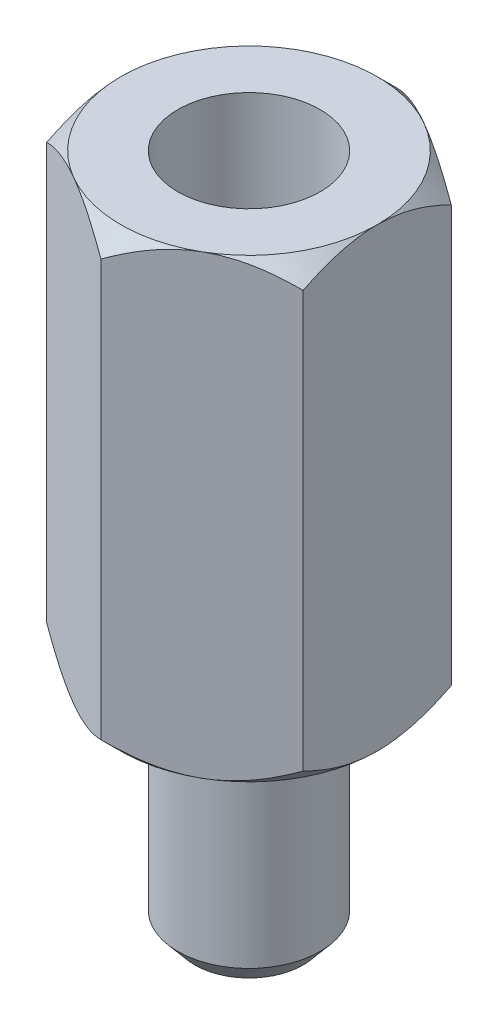
SolidWorks part; units mm, degrees
ref_plane "Front Plane" through (0, 0, 0) normal (0, 0, 1) x (1, 0, 0)
ref_plane "Top Plane" through (0, 0, 0) normal (0, 1, 0) x (1, 0, 0)
ref_plane "Right Plane" through (0, 0, 0) normal (1, 0, 0) x (0, 0, -1)
sketch "Sketch1" plane through (0, 0, 0) normal (0, 1, 0) x (1, 0, 0)
  circle A0 centre (0, 0) radius 1.25
  dimension "D1" = 2.5
extrude "Boss-Extrude1" add sketch "Sketch1" along normal blind 3.9
sketch "Sketch2" plane through (0, 3.9, 0) normal (0, 1, 0) x (1, 0, 0)
  line L1 (-2.25, 1.299) -> (-2.25, -1.299)
  line L2 (-2.25, -1.299) -> (0, -2.5981)
  line L3 (0, -2.5981) -> (2.25, -1.299)
  line L4 (2.25, -1.299) -> (2.25, 1.299)
  line L5 (2.25, 1.299) -> (0, 2.5981)
  line L6 (0, 2.5981) -> (-2.25, 1.299)
  circle A0 centre (0, 0) radius 2.25 construction
  dimension "D1" = 4.5
extrude "Boss-Extrude2" add sketch "Sketch2" along normal blind 8
sketch "Sketch3" plane through (0, 11.9, 0) normal (0, 1, 0) x (1, 0, 0)
  circle A0 centre (0, 0) radius 1.25
  dimension "D1" = 2.5
extrude "Cut-Extrude1" cut sketch "Sketch3" against normal blind 4.8
sketch "Sketch5" plane through (0, 11.9, 0) normal (0, 1, 0) x (1, 0, 0)
  circle A0 centre (0, 0) radius 2.25
extrude "Cut-Extrude2" cut sketch "Sketch5" against normal through all draft 45 flip side to cut
sketch "Sketch6" plane through (0, 3.9, 0) normal (0, -1, 0) x (1, 0, 0)
  circle A0 centre (0, 0) radius 2.25
extrude "Cut-Extrude3" cut sketch "Sketch6" against normal through all draft 45 flip side to cut
chamfer "Chamfer1" distance 0.3 angle 50 1 edges at (0, 0, 1.25)
